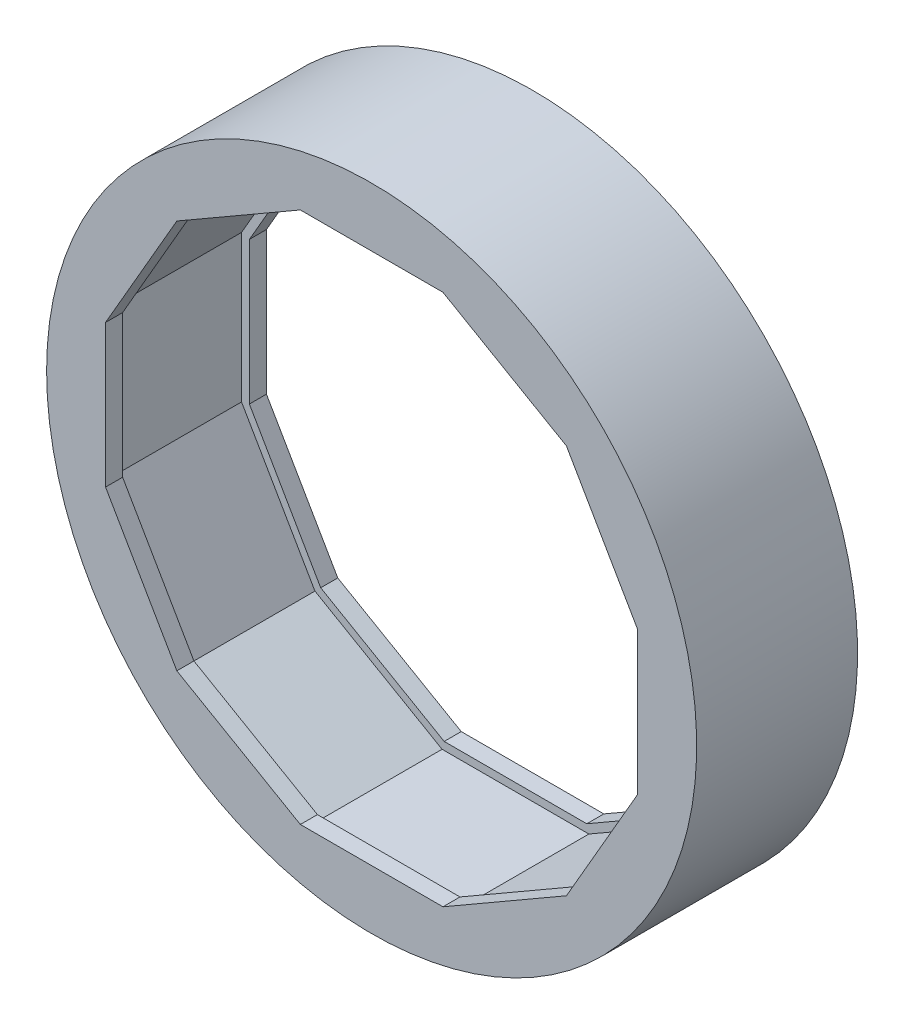
SolidWorks part; units mm, degrees
ref_plane "Front Plane" through (0, 0, 0) normal (0, 0, 1) x (1, 0, 0)
ref_plane "Top Plane" through (0, 0, 0) normal (0, 1, 0) x (1, 0, 0)
ref_plane "Right Plane" through (0, 0, 0) normal (1, 0, 0) x (0, 0, -1)
sketch "S01 - 80 mm tyre and two inward bead lips" plane through (0, 0, 0) normal (0, 0, 1) x (1, 0, 0)
  line L0 (32.7449, 8.774) -> (23.9709, 23.9709)
  line L1 (23.9709, 23.9709) -> (8.774, 32.7449)
  line L2 (8.774, 32.7449) -> (-8.774, 32.7449)
  line L3 (-8.774, 32.7449) -> (-23.9709, 23.9709)
  line L4 (-23.9709, 23.9709) -> (-32.7449, 8.774)
  line L5 (-32.7449, 8.774) -> (-32.7449, -8.774)
  line L6 (-32.7449, -8.774) -> (-23.9709, -23.9709)
  line L7 (-23.9709, -23.9709) -> (-8.774, -32.7449)
  line L8 (-8.774, -32.7449) -> (8.774, -32.7449)
  line L9 (8.774, -32.7449) -> (23.9709, -23.9709)
  line L10 (23.9709, -23.9709) -> (32.7449, -8.774)
  line L11 (32.7449, -8.774) -> (32.7449, 8.774)
  circle A0 centre (0, 0) radius 40
  dimension "D1" = 80
  dimension "D2" = 8.774
  dimension "D3" = 23.9709
  dimension "D4" = 32.7449
  dimension "D5" = 8.774
  dimension "D6" = 23.9709
  dimension "D7" = 32.7449
  dimension "D8" = 8.774
  dimension "D9" = 23.9709
  dimension "D10" = 32.7449
  dimension "D11" = 8.774
  dimension "D12" = 23.9709
  dimension "D13" = 32.7449
extrude "01 - 80 mm tyre and two inward bead lips" add sketch "S01 - 80 mm tyre and two inward bead lips" along normal blind 19.8
sketch "S02 - Central keyed drive recess between end beads" plane through (0, 0, 0) normal (0, 0, 1) x (1, 0, 0)
  line L0 (33.7108, 9.0328) -> (24.678, 24.678)
  line L1 (24.678, 24.678) -> (9.0328, 33.7108)
  line L2 (9.0328, 33.7108) -> (-9.0328, 33.7108)
  line L3 (-9.0328, 33.7108) -> (-24.678, 24.678)
  line L4 (-24.678, 24.678) -> (-33.7108, 9.0328)
  line L5 (-33.7108, 9.0328) -> (-33.7108, -9.0328)
  line L6 (-33.7108, -9.0328) -> (-24.678, -24.678)
  line L7 (-24.678, -24.678) -> (-9.0328, -33.7108)
  line L8 (-9.0328, -33.7108) -> (9.0328, -33.7108)
  line L9 (9.0328, -33.7108) -> (24.678, -24.678)
  line L10 (24.678, -24.678) -> (33.7108, -9.0328)
  line L11 (33.7108, -9.0328) -> (33.7108, 9.0328)
  dimension "D1" = 9.0328
  dimension "D2" = 24.678
  dimension "D3" = 33.7108
  dimension "D4" = 9.0328
  dimension "D5" = 24.678
  dimension "D6" = 33.7108
  dimension "D7" = 9.0328
  dimension "D8" = 24.678
  dimension "D9" = 33.7108
  dimension "D10" = 9.0328
  dimension "D11" = 24.678
  dimension "D12" = 33.7108
extrude "02 - Central keyed drive recess between end beads" cut sketch "S02 - Central keyed drive recess between end beads" along normal blind 15.6 from offset 2.1
